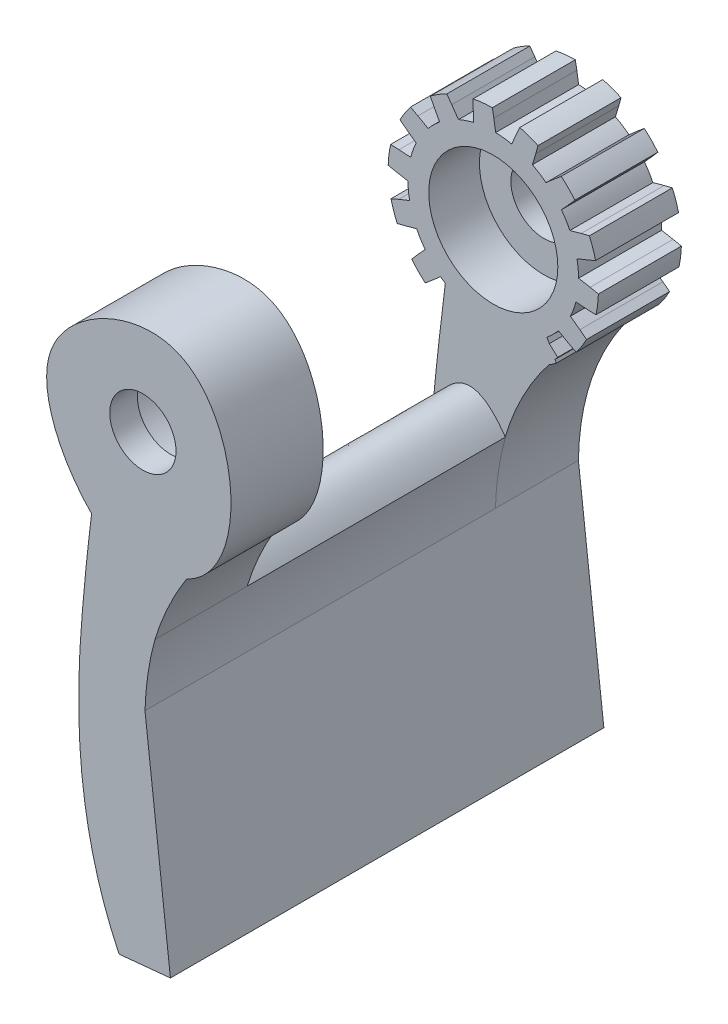
SolidWorks part; units mm, degrees
ref_plane "Front Plane" through (0, 0, 0) normal (0, 0, 1) x (1, 0, 0)
ref_plane "Top Plane" through (0, 0, 0) normal (0, 1, 0) x (1, 0, 0)
ref_plane "Right Plane" through (0, 0, 0) normal (1, 0, 0) x (0, 0, -1)
sketch "Sketch2" plane through (0, 0, 0) normal (0, 0, 1) x (1, 0, 0)
  line L595 (17.593, 3.4479) -> (18.4327, 3.8121)
  line L596 (16.415, 2.9762) -> (17.593, 3.4479)
  line L597 (15.6491, 5.2416) -> (16.8717, 5.5815)
  line L598 (16.8717, 5.5815) -> (17.7601, 5.8015)
  line L599 (5.2228, 10.175) -> (5.1635, 11.4426)
  line L600 (5.1635, 11.4426) -> (5.1467, 12.3577)
  line L601 (11.588, 9.3895) -> (11.9537, 10.6047)
  line L602 (11.9537, 10.6047) -> (12.1925, 11.4882)
  line L603 (9.3394, 10.2032) -> (9.8359, 11.371)
  line L604 (9.8359, 11.371) -> (10.2178, 12.2028)
  line L605 (14.7334, 6.7337) -> (15.5901, 7.6699)
  line L606 (15.5901, 7.6699) -> (16.1886, 8.3623)
  line L607 (13.0605, 8.4425) -> (14.0145, 9.2792)
  line L608 (14.0145, 9.2792) -> (14.7195, 9.8629)
  line L609 (-1.907, 1.1079) -> (-3.156, 1.3322)
  line L610 (-3.156, 1.3322) -> (-4.0519, 1.5194)
  line L611 (0.2752, 7.1388) -> (-0.8281, 7.7657)
  line L612 (-0.8281, 7.7657) -> (-1.6364, 8.1951)
  line L613 (-1.0184, 5.1275) -> (-2.0464, 5.8715)
  line L614 (-2.0464, 5.8715) -> (-2.7724, 6.4289)
  line L615 (3.5643, 9.6143) -> (2.8423, 10.6578)
  line L616 (2.8423, 10.6578) -> (2.3004, 11.3954)
  line L617 (1.5262, 8.3635) -> (0.9228, 9.4798)
  line L618 (0.9228, 9.4798) -> (0.5105, 10.297)
  line L619 (7.6018, 10.4176) -> (7.4041, 11.6711)
  line L620 (7.4041, 11.6711) -> (7.2358, 12.5707)
  line L621 (-0.0478, -4.3913) -> (-0.9045, -5.3274)
  line L622 (-0.9045, -5.3274) -> (-1.503, -6.0199)
  line L623 (1.6251, -6.1) -> (0.6711, -6.9367)
  line L624 (0.6711, -6.9367) -> (-0.0339, -7.5204)
  line L625 (-1.7294, -0.6337) -> (-2.9074, -1.1055)
  line L626 (-2.9074, -1.1055) -> (-3.7471, -1.4697)
  line L627 (-0.9635, -2.8991) -> (-2.1861, -3.239)
  line L628 (-2.1861, -3.239) -> (-3.0745, -3.459)
  line L629 (-1.6141, 3.4813) -> (-2.8801, 3.5674)
  line L630 (-2.8801, 3.5674) -> (-3.7947, 3.6036)
  line L631 (13.1594, -6.0211) -> (13.7628, -7.1374)
  line L632 (13.7628, -7.1374) -> (14.1751, -7.9546)
  line L633 (7.0838, -8.0751) -> (7.2815, -9.3286)
  line L634 (7.2815, -9.3286) -> (7.4497, -10.2283)
  line L635 (9.4628, -7.8326) -> (9.5221, -9.1001)
  line L636 (9.5221, -9.1001) -> (9.5389, -10.0152)
  line L637 (3.0976, -7.0471) -> (2.7319, -8.2622)
  line L638 (2.7319, -8.2622) -> (2.4931, -9.1458)
  line L639 (5.3462, -7.8607) -> (4.8497, -9.0285)
  line L640 (4.8497, -9.0285) -> (4.4678, -9.8603)
  line L641 (16.2997, -1.1388) -> (17.5657, -1.2249)
  line L642 (17.5657, -1.2249) -> (18.4803, -1.2611)
  line L643 (16.5926, 1.2345) -> (17.8416, 1.0103)
  line L644 (17.8416, 1.0103) -> (18.7375, 0.8231)
  line L645 (14.4104, -4.7963) -> (15.5137, -5.4232)
  line L646 (15.5137, -5.4232) -> (16.322, -5.8526)
  line L647 (15.704, -2.7851) -> (16.732, -3.529)
  line L648 (16.732, -3.529) -> (17.458, -4.0864)
  line L649 (11.1213, -7.2719) -> (11.8433, -8.3154)
  line L650 (11.8433, -8.3154) -> (12.3852, -9.053)
  arc A45 (12.3852, -9.053) -> (14.1751, -7.9546) centre (7.3428, 1.1712) ccw
  arc A46 (7.4497, -10.2283) -> (9.5389, -10.0152) centre (7.3428, 1.1712) ccw
  arc A48 (2.4931, -9.1458) -> (4.4678, -9.8603) centre (7.3428, 1.1712) ccw
  arc A50 (-1.503, -6.0199) -> (-0.0339, -7.5204) centre (7.3428, 1.1712) ccw
  arc A51 (5.3462, -7.8607) -> (7.0838, -8.0751) centre (7.3428, 1.1712) ccw
  arc A52 (-3.7471, -1.4697) -> (-3.0745, -3.459) centre (7.3428, 1.1712) ccw
  arc A53 (-3.7947, 3.6036) -> (-4.0519, 1.5194) centre (7.3428, 1.1712) ccw
  arc A54 (-1.6364, 8.1951) -> (-2.7724, 6.4289) centre (7.3428, 1.1712) ccw
  arc A55 (2.3004, 11.3954) -> (0.5105, 10.297) centre (7.3428, 1.1712) ccw
  arc A56 (7.2358, 12.5707) -> (5.1467, 12.3577) centre (7.3428, 1.1712) ccw
  arc A57 (12.1925, 11.4882) -> (10.2178, 12.2028) centre (7.3428, 1.1712) ccw
  arc A58 (16.1886, 8.3623) -> (14.7195, 9.8629) centre (7.3428, 1.1712) ccw
  arc A59 (18.4327, 3.8121) -> (17.7601, 5.8015) centre (7.3428, 1.1712) ccw
  arc A60 (18.4803, -1.2611) -> (18.7375, 0.8231) centre (7.3428, 1.1712) ccw
  arc A61 (16.322, -5.8526) -> (17.458, -4.0864) centre (7.3428, 1.1712) ccw
  arc A62 (1.6251, -6.1) -> (3.0976, -7.0471) centre (7.3428, 1.1712) ccw
  arc A63 (-0.9635, -2.8991) -> (-0.0478, -4.3913) centre (7.3428, 1.1712) ccw
  arc A64 (-1.907, 1.1079) -> (-1.7294, -0.6337) centre (7.3428, 1.1712) ccw
  arc A65 (-1.0184, 5.1275) -> (-1.6141, 3.4813) centre (7.3428, 1.1712) ccw
  arc A66 (1.5262, 8.3635) -> (0.2752, 7.1388) centre (7.3428, 1.1712) ccw
  arc A67 (5.2228, 10.175) -> (3.5643, 9.6143) centre (7.3428, 1.1712) ccw
  arc A68 (9.3394, 10.2032) -> (7.6018, 10.4176) centre (7.3428, 1.1712) ccw
  arc A69 (13.0605, 8.4425) -> (11.588, 9.3895) centre (7.3428, 1.1712) ccw
  arc A70 (15.6491, 5.2416) -> (14.7334, 6.7337) centre (7.3428, 1.1712) ccw
  arc A71 (16.5926, 1.2345) -> (16.415, 2.9762) centre (7.3428, 1.1712) ccw
  arc A72 (15.704, -2.7851) -> (16.2997, -1.1388) centre (7.3428, 1.1712) ccw
  arc A73 (13.1594, -6.0211) -> (14.4104, -4.7963) centre (7.3428, 1.1712) ccw
  arc A74 (9.4628, -7.8326) -> (11.1213, -7.2719) centre (7.3428, 1.1712) ccw
extrude "Boss-Extrude1" add sketch "Sketch2" against normal blind 7 and the other way blind 2
sketch "Sketch5" plane through (0, 0, 2) normal (0, 0, 1) x (1, 0, 0)
  line L0 (14.3231, -7.3303) -> (11.4972, -4.736)
  line L1 (11.4711, 11.5) -> (18.1778, 11.5) construction
  line L5 (11.4972, -4.736) -> (2.3486, -4.736)
  line L6 (4.7635, -49.1601) -> (10.3329, -48.6138)
  line L8 (10.3329, -48.6138) -> (7.5745, -24.8887)
  spline S0 degree 2 poles (14.3231, -7.3303) (7.7593, -14.9756) (7.5745, -24.8887) knots 0 0 0 1 1 1
  spline S1 degree 3 poles (2.3486, -4.736) (0.6286, -19.3279) (-1.9127, -35.3615) (4.7635, -49.1601) knots 0 0 0 0 1 1 1 1
  point P6 (14.3231, -7.3303)
  point P7 (11.4972, -4.736)
extrude "Boss-Extrude3" add sketch "Sketch5" against normal up to surface (9 mm away) up to face at (7.3428, 1.1712, -7)
sketch "Sketch6" plane through (0, 0, -7) normal (0, 0, -1) x (-1, 0, 0)
  circle A1 centre (-7.3428, 1.1712) radius 7
  circle A2 centre (-7.3428, 1.1712) radius 3.6969
extrude "Boss-Extrude4" add sketch "Sketch6" against normal blind 3
sketch "Sketch7" plane through (0, 0, 2) normal (0, 0, 1) x (1, 0, 0)
  line L161 (4.7635, -49.1601) -> (10.3329, -48.6138)
  line L162 (10.3329, -48.6138) -> (7.5745, -24.8887)
  parabola Q2 (7.5745, -24.8887) -> (8.6538, -17.6601) focus (22.7723, -21.0221) apex (8.9649, -16.6175)
  spline S0 degree 2 poles (0.854, -18.1722) (4.5116, -11.6662) (8.6538, -17.6601) knots 0 0 0 1 1 1
  spline S2 degree 3 poles (0.854, -18.1722) (-0.1328, -28.7368) (0.1232, -39.5133) (4.7635, -49.1601) knots 0.275802 0.275802 0.275802 0.275802 1 1 1 1
extrude "Boss-Extrude5" add sketch "Sketch7" along normal blind 38
sketch "Sketch8" plane through (0, 0, 40) normal (0, 0, 1) x (1, 0, 0)
  circle A1 centre (7.3428, 1.1712) radius 7
  parabola Q0 (8.6458, -17.6486) -> (13.3554, -8.5143) focus (21.4277, -20.5379) apex (9.1243, -16.1637) construction
  parabola Q5 (8.1615, -19.4857) -> (12.1031, -10.2512) focus (22.6855, -21.368) apex (8.9905, -16.6255)
  parabola Q20 (0.7809, -18.9822) -> (8.1615, -19.4857) focus (4.5263, -16.0548) apex (4.556, -15.2068)
  spline S0 degree 3 poles (1.7845, -9.2947) (-1.2851, -6.2275) (-7.4671, 5.2774) (17.0208, 17.7449) (19.3837, -6.8055) (12.1031, -10.2512) knots 0 0 0 0 0.273427 0.555145 1 1 1 1
  spline S2 degree 3 poles (1.7845, -9.2947) (1.3927, -12.4844) (1.0326, -15.725) (0.7809, -18.9822) knots 0.071303 0.071303 0.071303 0.071303 0.275802 0.275802 0.275802 0.275802
  point P2 (0.854, -18.1722)
  point P5 (0, 0)
  point P6 (0, 0)
  point P10 (0, 0)
  point P11 (0, 0)
  point P12 (4.4723, -15.273)
  point P13 (0.7809, -18.9822)
  point P14 (0, 0)
  point P15 (0, 0)
  point P22 (12.1031, -10.2512)
  point P51 (1.9165, -9.3033)
  point P55 (0, 0)
  spline M138 degree 2 poles (8.6538, -17.6601) (4.5116, -11.6662) (0.854, -18.1722) knots 0 0 0 1 1 1
extrude "Boss-Extrude6" add sketch "Sketch8" against normal blind 10 contours S0 S2 Q5 A1 M138
sketch "Sketch9" plane through (0, 0, 40) normal (0, 0, 1) x (1, 0, 0)
  circle A1 centre (7.3428, 1.1712) radius 7
  circle A2 centre (7.3428, 1.1712) radius 3.5916
extrude "Boss-Extrude7" add sketch "Sketch9" against normal blind 3
sketch "Sketch10" plane through (0, 0, 2) normal (0, 0, 1) x (1, 0, 0)
  circle A0 centre (7.3428, 1.1712) radius 7 construction
  circle A1 centre (7.3428, 1.1712) radius 7
extrude "Cut-Extrude1" cut sketch "Sketch10" against normal blind 5.5
sketch "Sketch11" plane through (0, 0, -7) normal (0, 0, -1) x (-1, 0, 0)
  circle A0 centre (-7.3428, 1.1712) radius 3.5916 construction
  circle A1 centre (-7.3428, 1.1712) radius 3.5916
extrude "Cut-Extrude2" cut sketch "Sketch11" against normal through all
